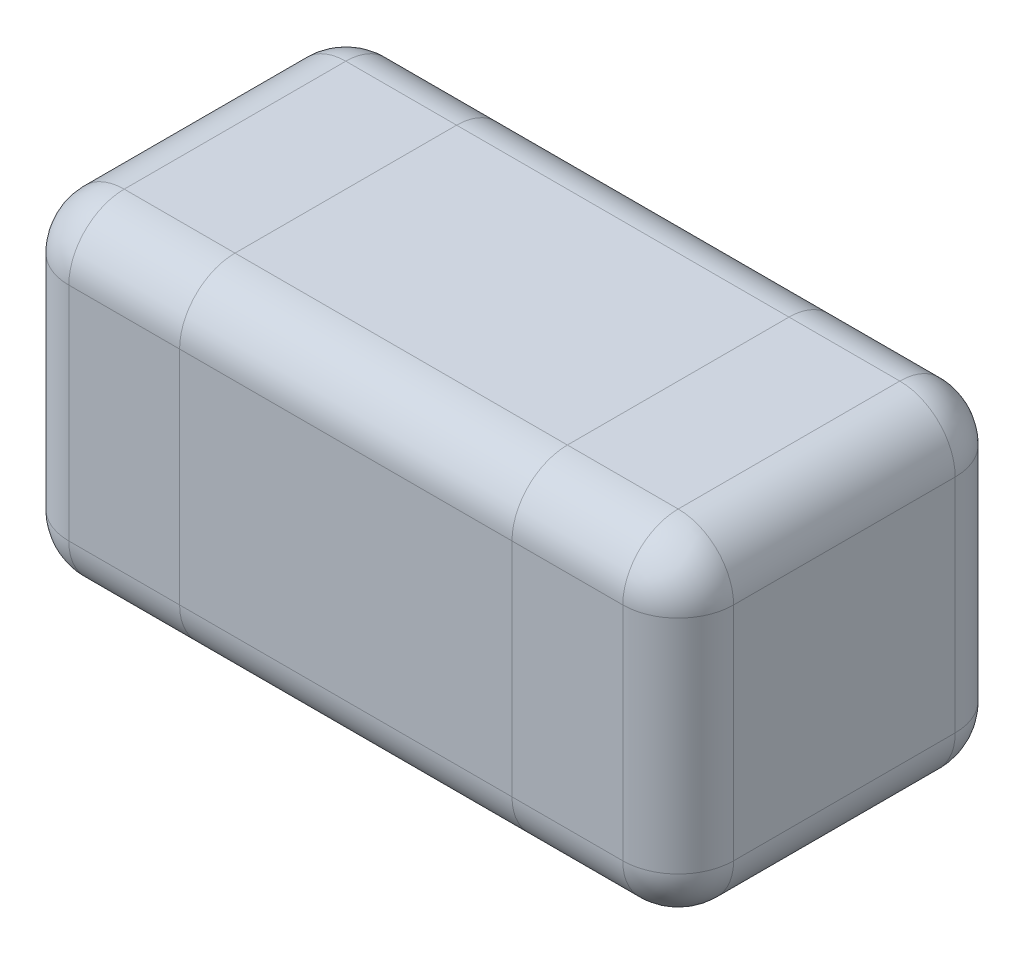
SolidWorks part; units mm, degrees
ref_plane "Alzado" through (0, 0, 0) normal (0, 0, 1) x (1, 0, 0)
ref_plane "Planta" through (0, 0, 0) normal (0, 1, 0) x (1, 0, 0)
ref_plane "Vista lateral" through (0, 0, 0) normal (1, 0, 0) x (0, 0, -1)
sketch "Croquis1" plane through (0, 0, 0) normal (0, 1, 0) x (1, 0, 0)
  line L1 (-0.15, -0.15) -> (0.15, -0.15)
  line L2 (-0.15, -0.15) -> (-0.15, 0.15)
  line L3 (-0.15, 0.15) -> (0.15, 0.15)
  line L4 (0.15, -0.15) -> (0.15, 0.15)
  line L5 (-0.15, -0.15) -> (0.15, 0.15) construction
  line L6 (-0.15, 0.15) -> (0.15, -0.15) construction
  point P0 (0, 0)
  dimension "D1" = 0.3
  dimension "D2" = 0.3
extrude "Saliente-Extruir1" add sketch "Croquis1" along normal blind 0.3
sketch "Croquis3" plane through (0, 0, 0) normal (0, 1, 0) x (1, 0, 0)
  line L0 (0.15, 0.15) -> (0.3, 0.15)
  line L1 (0.3, 0.15) -> (0.3, -0.15)
  line L2 (0.3, -0.15) -> (0.15, -0.15)
  line L3 (0.15, -0.15) -> (0.15, 0.15) construction
  line L4 (0.15, -0.15) -> (0.15, 0.15)
  line L5 (0, 1.3421) -> (0, -1.4057) construction
  line L6 (-0.15, -0.15) -> (-0.15, 0.15)
  line L7 (-0.3, -0.15) -> (-0.15, -0.15)
  line L8 (-0.3, 0.15) -> (-0.3, -0.15)
  line L9 (-0.15, 0.15) -> (-0.3, 0.15)
  dimension "D1" = 0.15
extrude "Saliente-Extruir3" add sketch "Croquis3" along normal blind 0.3 separate body
fillet "Redondeo2" radius 0.05 4 edges at (0, 0, 0.15) (0, 0.3, 0.15) (0, 0, -0.15) (0, 0.3, -0.15)
fillet "Redondeo4" radius 0.05 8 edges at (0.3, 0.15, 0.15) (0.3, 0.3, 0) (0.3, 0.15, -0.15) (0.3, 0, 0) (0.225, 0, 0.15) (0.225, 0.3, 0.15) (0.225, 0.3, -0.15) (0.225, 0, -0.15)
fillet "Redondeo5" radius 0.05 8 edges at (-0.3, 0.15, -0.15) (-0.3, 0.3, 0) (-0.3, 0.15, 0.15) (-0.3, 0, 0) (-0.225, 0, -0.15) (-0.225, 0.3, -0.15) (-0.225, 0, 0.15) (-0.225, 0.3, 0.15)
